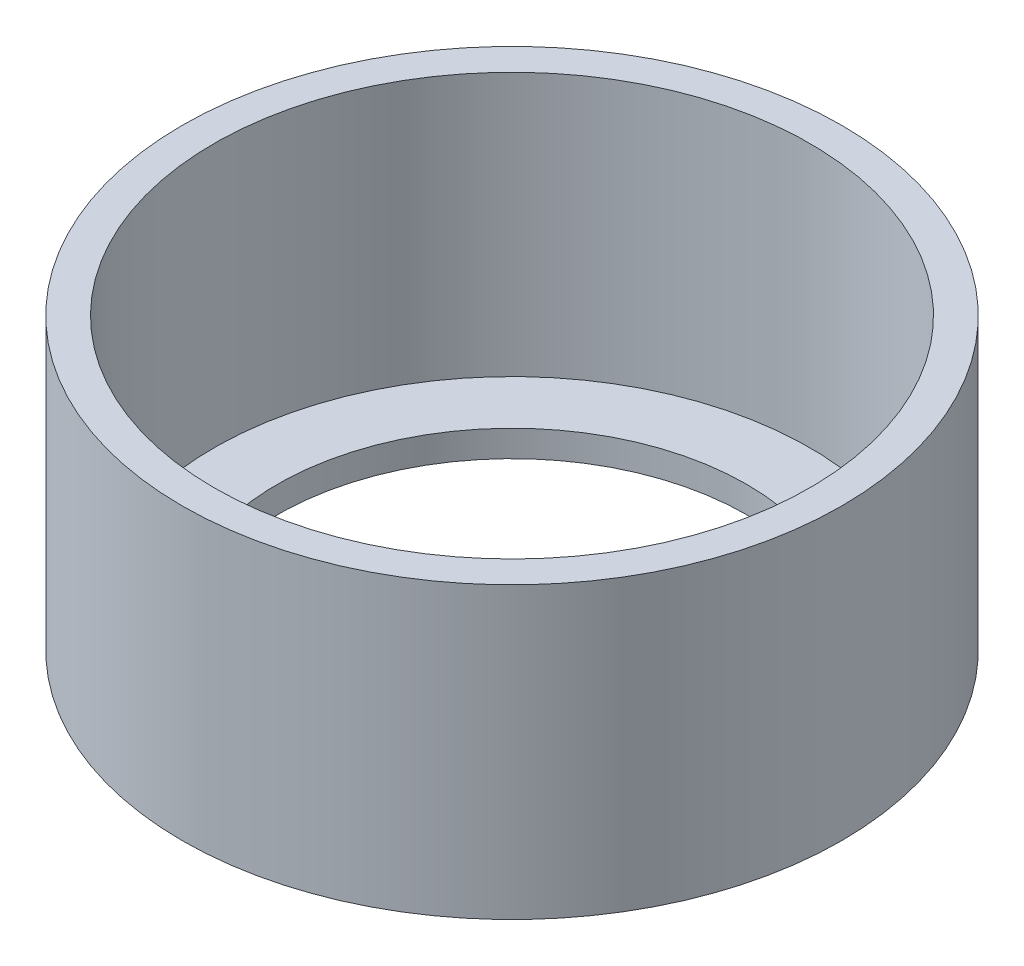
SolidWorks part; units mm, degrees
material "ABS"
ref_plane "Alzado" through (0, 0, 0) normal (0, 0, 1) x (1, 0, 0)
ref_plane "Planta" through (0, 0, 0) normal (0, 1, 0) x (1, 0, 0)
ref_plane "Vista lateral" through (0, 0, 0) normal (1, 0, 0) x (0, 0, -1)
sketch "Croquis1" plane through (0, 0, 0) normal (0, 1, 0) x (1, 0, 0)
  circle A0 centre (0, 0) radius 5.655
  circle A1 centre (0, 0) radius 6.255
  dimension "D1" = 11.31
  dimension "D2" = 0.6
extrude "Saliente-Extruir1" add sketch "Croquis1" along normal blind 5
sketch "Croquis2" plane through (0, 0, 0) normal (0, -1, 0) x (1, 0, 0)
  circle A0 centre (0, 0) radius 6.255
  circle A1 centre (0, 0) radius 4.455
  circle A2 centre (0, 0) radius 6.255 construction
  circle A3 centre (0, 0) radius 5.655 construction
  dimension "D1" = 1.2
extrude "Saliente-Extruir2" add sketch "Croquis2" along normal blind 0.5
